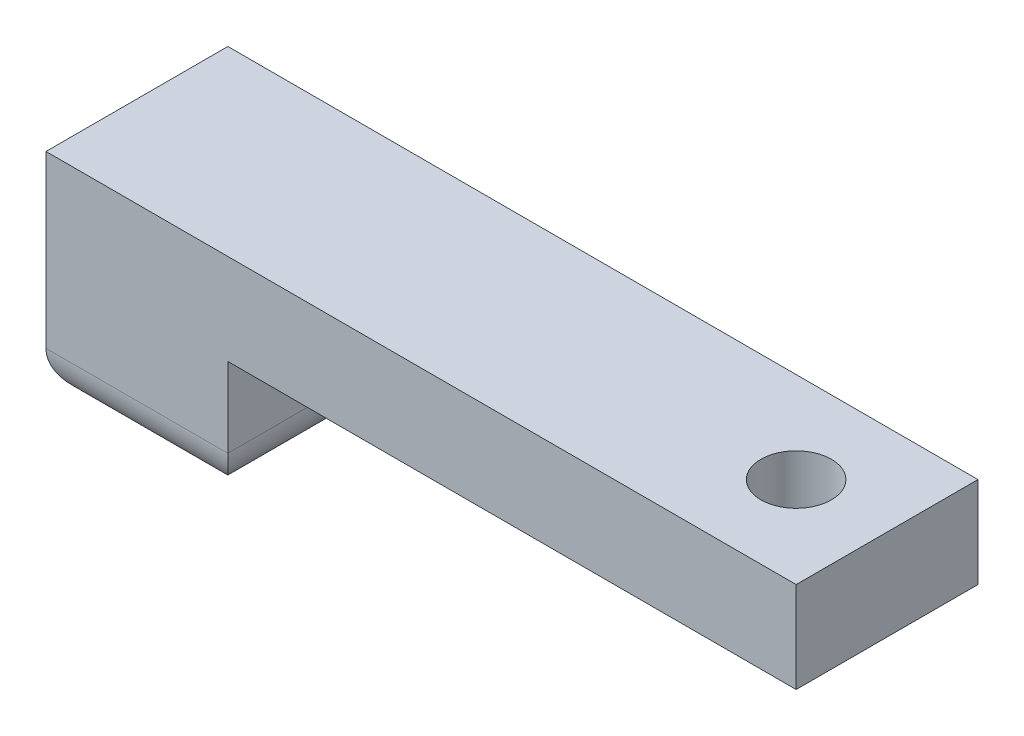
SolidWorks part; units mm, degrees
ref_plane "Front Plane" through (0, 0, 0) normal (0, 0, 1) x (1, 0, 0)
ref_plane "Top Plane" through (0, 0, 0) normal (0, 1, 0) x (1, 0, 0)
ref_plane "Right Plane" through (0, 0, 0) normal (1, 0, 0) x (0, 0, -1)
sketch "Sketch1" plane through (0, 0, 0) normal (0, 1, 0) x (1, 0, 0)
  line L1 (-16.2813, 6.3281) -> (16.7187, 6.3281)
  line L2 (-16.2813, 6.3281) -> (-16.2813, -1.6719)
  line L3 (-16.2813, -1.6719) -> (16.7187, -1.6719)
  line L4 (16.7187, 6.3281) -> (16.7187, -1.6719)
  circle A0 centre (12.7187, 2.3281) radius 1.55
  dimension "D3" = 4
  dimension "D1" = 33
  dimension "D2" = 8
extrude "Boss-Extrude1" add sketch "Sketch1" along normal blind 4
sketch "Sketch3" plane through (0, 0, 0) normal (0, -1, 0) x (1, 0, 0)
  line L0 (16.7187, -6.3281) -> (-16.2813, -6.3281) construction
  line L1 (-16.2813, 1.6719) -> (-8.2813, 1.6719)
  line L2 (-16.2813, 1.6719) -> (-16.2813, -6.3281)
  line L3 (-16.2813, -6.3281) -> (-8.2813, -6.3281)
  line L4 (-8.2813, 1.6719) -> (-8.2813, -6.3281)
  dimension "D1" = 8
extrude "Boss-Extrude2" add sketch "Sketch3" along normal blind 5.5
fillet "Fillet1" radius 2 4 edges at (-12.2813, -5.5, 1.6719) (-8.2813, -5.5, -2.3281) (-12.2813, -5.5, -6.3281) (-16.2813, -5.5, -2.3281)
